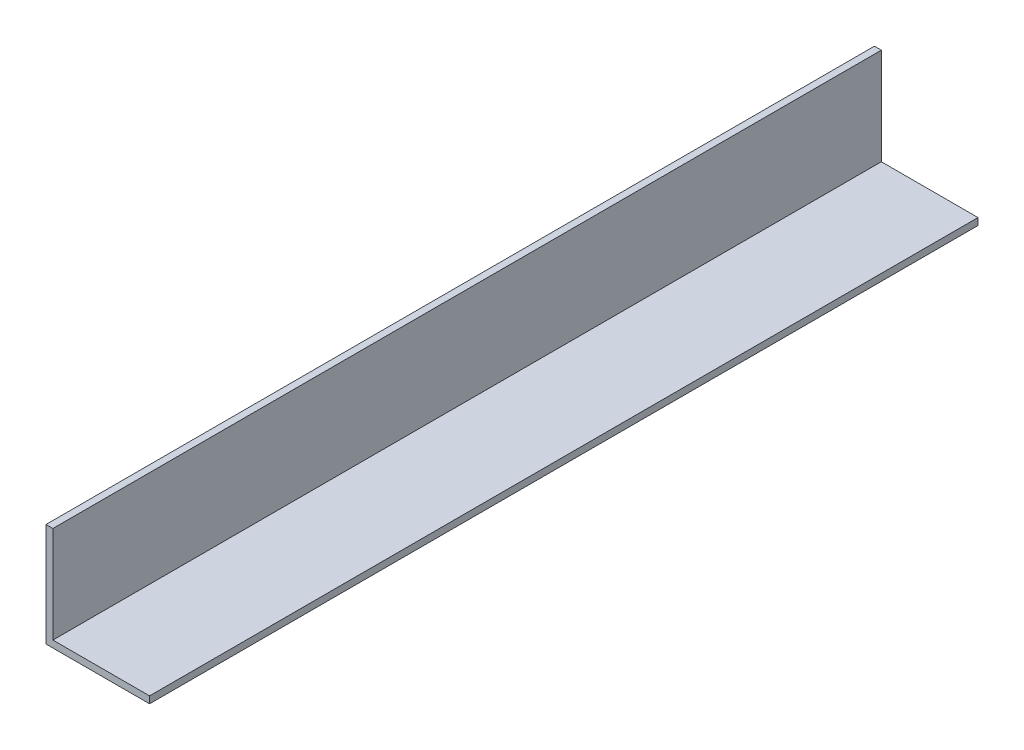
SolidWorks part; units mm, degrees
ref_plane "Спереди" through (0, 0, 0) normal (0, 0, 1) x (1, 0, 0)
ref_plane "Сверху" through (0, 0, 0) normal (0, 1, 0) x (1, 0, 0)
ref_plane "Справа" through (0, 0, 0) normal (1, 0, 0) x (0, 0, -1)
sketch "Эскиз1" plane through (0, 0, 0) normal (0, 0, 1) x (1, 0, 0)
  line L0 (0, 0) -> (30, 0)
  line L1 (30, 0) -> (30, 2)
  line L2 (30, 2) -> (2, 2)
  line L3 (2, 2) -> (2, 30)
  line L4 (2, 30) -> (0, 30)
  line L5 (0, 30) -> (0, 0)
  dimension "D1" = 30
  dimension "D2" = 30
  dimension "D3" = 2
  dimension "D4" = 2
extrude "Бобышка-Вытянуть1" add sketch "Эскиз1" along normal blind 240
